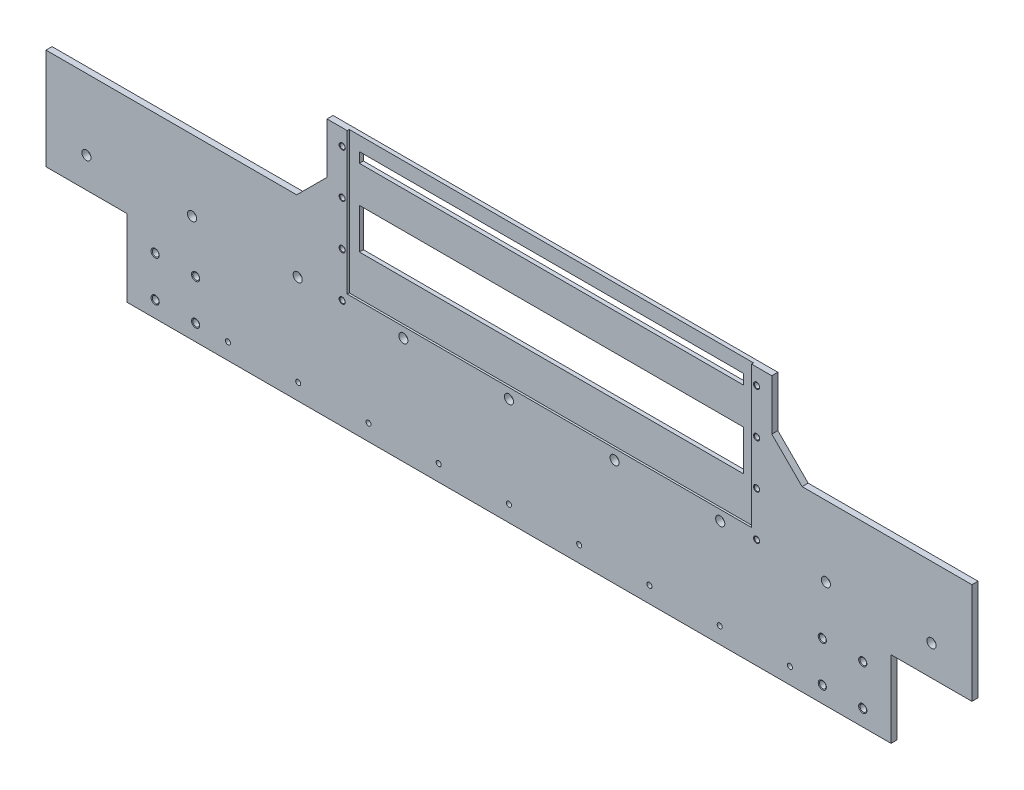
SolidWorks part; units mm, degrees
material "Д16Т ГОСТ 4784-74"
ref_plane "Спереди" through (0, 0, 0) normal (0, 0, 1) x (1, 0, 0)
ref_plane "Сверху" through (0, 0, 0) normal (0, 1, 0) x (1, 0, 0)
ref_plane "Справа" through (0, 0, 0) normal (1, 0, 0) x (0, 0, -1)
sketch "Эскиз1" plane through (0, 0, 0) normal (0, 0, 1) x (1, 0, 0)
  line L0 (259, 50) -> (298, 50)
  line L1 (0, 0) -> (298, 0)
  line L2 (0, 0) -> (0, 50)
  line L3 (0, 50) -> (39, 50)
  line L4 (298, 0) -> (298, 50)
  line L6 (39, 50) -> (39, 90)
  line L7 (39, 90) -> (259, 90)
  line L8 (259, 50) -> (259, 90)
  dimension "D1" = 298
  dimension "D2" = 50
  dimension "D3" = 90
  dimension "D4" = 220
extrude "Бобышка-Вытянуть1" add sketch "Эскиз1" along normal blind 3
sketch "Эскиз2" plane through (0, 0, 3) normal (0, 0, 1) x (1, 0, 0)
  line L0 (149, 90) -> (149, 83) construction
  line L1 (54, 83) -> (244, 83)
  line L2 (54, 83) -> (54, 78)
  line L3 (54, 78) -> (244, 78)
  line L4 (244, 83) -> (244, 78)
  line L5 (259, 90) -> (39, 90) construction
  line L6 (0, 0) -> (298, 0) construction
  line L7 (54, 60) -> (244, 60)
  line L8 (54, 60) -> (54, 40)
  line L9 (54, 40) -> (244, 40)
  line L10 (244, 60) -> (244, 40)
  dimension "D1" = 5
  dimension "D2" = 190
  dimension "D3" = 7
  dimension "D4" = 20
  dimension "D5" = 40
extrude "Вырез-Вытянуть1" cut sketch "Эскиз2" against normal blind 4
sketch "Эскиз3" plane through (0, 0, 3) normal (0, 0, 1) x (1, 0, 0)
  line L0 (259, 90) -> (39, 90) construction
  line L1 (49, 90) -> (249, 90)
  line L2 (49, 90) -> (49, 20)
  line L3 (49, 20) -> (249, 20)
  line L4 (249, 90) -> (249, 20)
  line L5 (54, 83) -> (54, 78) construction
  line L6 (54, 40) -> (244, 40) construction
  point P6 (149, 90)
  dimension "D1" = 5
  dimension "D2" = 20
extrude "Вырез-Вытянуть2" cut sketch "Эскиз3" against normal blind 1
sketch "Эскиз4" plane through (0, 0, 3) normal (0, 0, 1) x (1, 0, 0)
  line L2 (0, 50) -> (-100, 50)
  line L3 (0, 50) -> (0, 0)
  line L4 (-60, 0) -> (-100, 0)
  line L6 (-100, 50) -> (-100, 0)
  line L7 (298, 50) -> (358, 50)
  line L8 (298, 50) -> (298, 0)
  line L9 (318, 0) -> (358, 0)
  line L10 (358, 50) -> (358, 0)
  line L11 (0, 0) -> (298, 0)
  line L12 (-60, 0) -> (-60, -38)
  line L13 (-60, -38) -> (318, -38)
  line L14 (318, 0) -> (318, -38)
  dimension "D1" = 60
  dimension "D2" = 40
  dimension "D3" = 100
  dimension "D4" = 40
  dimension "D5" = 38
extrude "Бобышка-Вытянуть2" add sketch "Эскиз4" against normal up to surface (3 mm away) up to face at (149, 50, 0)
chamfer "Фаска1" distance 15 angle 45 2 edges at (39, 50, 1.5) (259, 50, 1.5)
hole_wizard "Отверстие обработанное метчиком M41" positions "Эскиз6" profile "Эскиз5" tap size "M4" standard "DIN"
sketch "Эскиз6" plane through (0, 0, 3) normal (0, 0, 1) x (1, 0, 0)
  line L0 (-60, -38) -> (318, -38) construction
  line L1 (-60, 0) -> (-60, -38) construction
  line L2 (-46, -30) -> (-26, -30) construction
  line L3 (-46, -30) -> (-46, -10) construction
  line L4 (129, -38) -> (129, 0) construction
  line L6 (304, -30) -> (304, -10) construction
  line L7 (304, -30) -> (284, -30) construction
  point P0 (-46, -30)
  point P12 (-26, -30)
  point P13 (-46, -10)
  point P14 (-26, -10)
  point P25 (284, -10)
  point P26 (304, -10)
  point P28 (304, -30)
  point P30 (284, -30)
  dimension "D1" = 8
  dimension "D2" = 14
  dimension "D5" = 90
  dimension "D6" = 20
  dimension "D7" = 20
  dimension "D3" = 2
  dimension "D4" = 2
sketch "Эскиз5" plane through (-46, -30, 3) normal (1, 0, 0) x (0, -1, 0)
  line L0 (0, 0) -> (0, 12.4914)
  line L1 (0, 12.4914) -> (1.65, 11.5)
  line L2 (1.65, 11.5) -> (1.65, 0.2165)
  line L3 (1.65, 0.2165) -> (2.025, 0)
  line L5 (2.025, 0) -> (0, 0)
  line L6 (-1.65, 0.2165) -> (-2.025, 0) construction
  line L10 (0, 12.4914) -> (-1.65, 11.5) construction
  line L11 (0, -6.35) -> (0, 107.95) construction
  dimension "Диаметр сверла" = 3.3
  dimension "Глубина сверла" = 11.5
  dimension "Диаметр передней зенковки" = 4.05
  dimension "Угол передней зенковки" = 120
  dimension "Угол заточки сверла" = 118
cosmetic thread "Отверстие резьбы1" parameters "D1"=3, "D2"=4
cosmetic thread "Отверстие резьбы2" parameters "D1"=3, "D2"=4
cosmetic thread "Отверстие резьбы3" parameters "D1"=3, "D2"=4
cosmetic thread "Отверстие резьбы4" parameters "D1"=3, "D2"=4
cosmetic thread "Отверстие резьбы5" parameters "D1"=3, "D2"=4
cosmetic thread "Отверстие резьбы6" parameters "D1"=3, "D2"=4
cosmetic thread "Отверстие резьбы7" parameters "D1"=3, "D2"=4
cosmetic thread "Отверстие резьбы8" parameters "D1"=3, "D2"=4
hole_wizard "Отверстие обработанное метчиком M31" positions "Эскиз8" profile "Эскиз7" tap size "M3" standard "DIN"
sketch "Эскиз8" plane through (0, 0, 0) normal (0, 0, -1) x (-1, 0, 0)
  line L0 (60, -38) -> (-318, -38) construction
  line L1 (-318, -38) -> (-318, 0) construction
  line L2 (-268, -30) -> (-233.25, -30) construction
  point P0 (-268, -30)
  point P12 (-233.25, -30)
  point P13 (-198.5, -30)
  point P14 (-163.75, -30)
  point P15 (-129, -30)
  point P16 (-94.25, -30)
  point P17 (-59.5, -30)
  point P18 (-24.75, -30)
  point P19 (10, -30)
  dimension "D1" = 8
  dimension "D2" = 50
  dimension "D4" = 34.75
  dimension "D3" = 9
sketch "Эскиз7" plane through (268, -30, 0) normal (1, 0, 0) x (0, 1, 0)
  line L0 (0, 0) -> (0, 9.2511)
  line L1 (0, 9.2511) -> (1.25, 8.5)
  line L2 (1.25, 8.5) -> (1.25, 0.1588)
  line L3 (1.25, 0.1588) -> (1.525, 0)
  line L5 (1.525, 0) -> (0, 0)
  line L6 (-1.25, 0.1588) -> (-1.525, 0) construction
  line L10 (0, 9.2511) -> (-1.25, 8.5) construction
  line L11 (0, -6.35) -> (0, 107.95) construction
  dimension "Диаметр сверла" = 2.5
  dimension "Глубина сверла" = 8.5
  dimension "Диаметр передней зенковки" = 3.05
  dimension "Угол передней зенковки" = 120
  dimension "Угол заточки сверла" = 118
cosmetic thread "Отверстие резьбы9" parameters "D1"=3, "D2"=3
cosmetic thread "Отверстие резьбы10" parameters "D1"=3, "D2"=3
cosmetic thread "Отверстие резьбы11" parameters "D1"=3, "D2"=3
cosmetic thread "Отверстие резьбы12" parameters "D1"=3, "D2"=3
cosmetic thread "Отверстие резьбы13" parameters "D1"=3, "D2"=3
cosmetic thread "Отверстие резьбы14" parameters "D1"=3, "D2"=3
cosmetic thread "Отверстие резьбы15" parameters "D1"=3, "D2"=3
cosmetic thread "Отверстие резьбы16" parameters "D1"=3, "D2"=3
cosmetic thread "Отверстие резьбы17" parameters "D1"=3, "D2"=3
hole_wizard "Отверстие обработанное метчиком M32" positions "Эскиз10" profile "Эскиз9" tap size "M3" standard "DIN"
sketch "Эскиз10" plane through (0, 0, 3) normal (0, 0, 1) x (1, 0, 0)
  line L0 (249, 20) -> (249, 90) construction
  line L1 (259, 90) -> (249, 90) construction
  line L2 (149, 20) -> (149, 96.3346) construction
  line L3 (49, 20) -> (249, 20) construction
  line L5 (251.5, 82) -> (251.5, 60) construction
  point P0 (251.5, 82)
  point P12 (46.5, 82)
  point P18 (251.5, 60)
  point P19 (46.5, 60)
  point P20 (251.5, 38)
  point P21 (46.5, 38)
  point P22 (251.5, 16)
  point P23 (46.5, 16)
  dimension "D1" = 2.5
  dimension "D2" = 8
  dimension "D3" = 4
  dimension "D4" = 22
sketch "Эскиз9" plane through (251.5, 82, 3) normal (1, 0, 0) x (0, -1, 0)
  line L0 (0, 0) -> (0, 9.2511)
  line L1 (0, 9.2511) -> (1.25, 8.5)
  line L2 (1.25, 8.5) -> (1.25, 0.1588)
  line L3 (1.25, 0.1588) -> (1.525, 0)
  line L5 (1.525, 0) -> (0, 0)
  line L6 (-1.25, 0.1588) -> (-1.525, 0) construction
  line L10 (0, 9.2511) -> (-1.25, 8.5) construction
  line L11 (0, -6.35) -> (0, 107.95) construction
  dimension "Диаметр сверла" = 2.5
  dimension "Глубина сверла" = 8.5
  dimension "Диаметр передней зенковки" = 3.05
  dimension "Угол передней зенковки" = 120
  dimension "Угол заточки сверла" = 118
cosmetic thread "Отверстие резьбы22" parameters "D1"=3, "D2"=3
cosmetic thread "Отверстие резьбы23" parameters "D1"=3, "D2"=3
cosmetic thread "Отверстие резьбы24" parameters "D1"=3, "D2"=3
cosmetic thread "Отверстие резьбы25" parameters "D1"=3, "D2"=3
cosmetic thread "Отверстие резьбы26" parameters "D1"=3, "D2"=3
cosmetic thread "Отверстие резьбы27" parameters "D1"=3, "D2"=3
cosmetic thread "Отверстие резьбы28" parameters "D1"=3, "D2"=3
cosmetic thread "Отверстие резьбы29" parameters "D1"=3, "D2"=3
hole_wizard "Отверстие с зазором M42" positions "Эскиз12" profile "Эскиз11" hole size "M4" standard "DIN"
sketch "Эскиз12" plane through (0, 0, 3) normal (0, 0, 1) x (1, 0, 0)
  line L0 (358, 0) -> (358, 50) construction
  line L1 (318, 0) -> (358, 0) construction
  line L2 (338, 15) -> (285.75, 15) construction
  point P0 (338, 15)
  point P15 (285.75, 15)
  point P16 (233.5, 15)
  point P17 (181.25, 15)
  point P18 (129, 15)
  point P19 (76.75, 15)
  point P20 (24.5, 15)
  point P21 (-27.75, 15)
  point P22 (-80, 15)
  dimension "D1" = 20
  dimension "D2" = 15
  dimension "D4" = 52.25
  dimension "D3" = 9
sketch "Эскиз11" plane through (338, 15, 3) normal (1, 0, 0) x (0, -1, 0)
  line L0 (0, 0) -> (0, 6.3519)
  line L1 (0, 6.3519) -> (2.25, 5)
  line L2 (2.25, 5) -> (2.25, 0)
  line L5 (2.25, 0) -> (0, 0)
  line L10 (0, 6.3519) -> (-2.25, 5) construction
  line L11 (0, -6.35) -> (0, 107.95) construction
  dimension "Диаметр отверстия" = 4.5
  dimension "Глубина отверстия" = 5
  dimension "Угол заточки сверла" = 118
